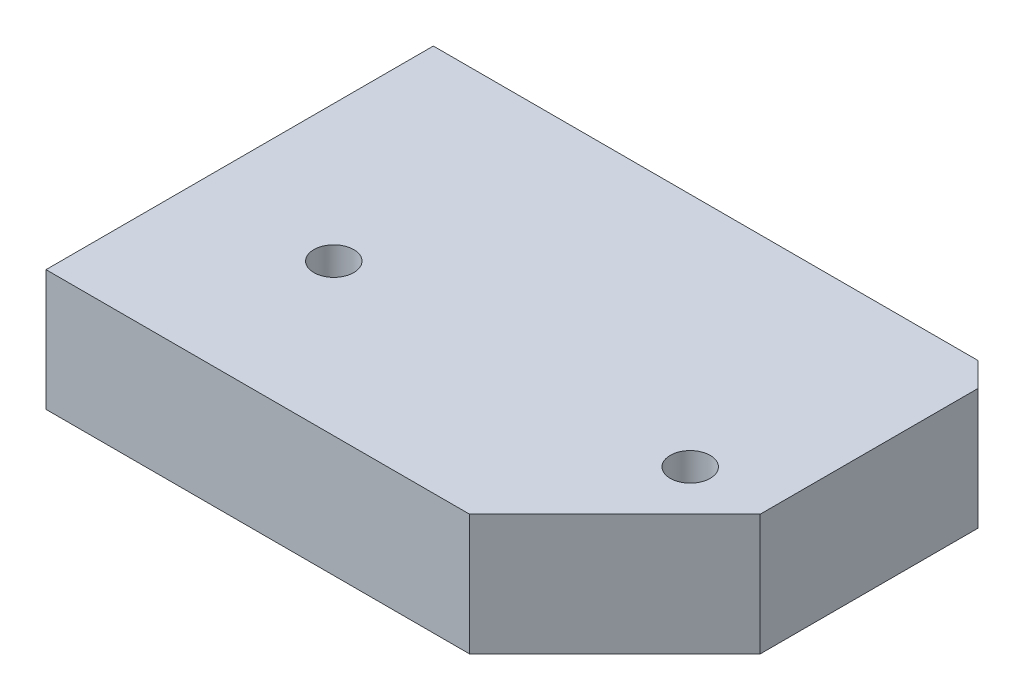
SolidWorks part; units mm, degrees
material "6061"
ref_plane "前视" through (0, 0, 0) normal (0, 0, 1) x (1, 0, 0)
ref_plane "上视" through (0, 0, 0) normal (0, 1, 0) x (1, 0, 0)
ref_plane "右视" through (0, 0, 0) normal (1, 0, 0) x (0, 0, -1)
sketch "草图1" plane through (0, 0, 0) normal (1, 0, 0) x (0, 0, -1)
  line L1 (-21, -5) -> (21, -5)
  line L2 (-21, -5) -> (-21, 5)
  line L3 (-21, 5) -> (21, 5)
  line L4 (21, -5) -> (21, 5)
  line L5 (-21, -5) -> (21, 5) construction
  line L6 (-21, 5) -> (21, -5) construction
  point P0 (0, 0)
  dimension "D1" = 42
  dimension "D2" = 10
extrude "凸台-拉伸1" add sketch "草图1" along normal mid plane 47
sketch "草图2" plane through (23.5, 0, 0) normal (1, 0, 0) x (0, 0, -1)
  line L0 (21, -5) -> (11, 5)
  line L1 (21, 5) -> (-21, 5) construction
  line L2 (11, 5) -> (21, 5)
  line L3 (21, 5) -> (21, -5)
extrude "切除-拉伸1" cut sketch "草图2" against normal through all
hole_wizard "M4 螺纹孔2" positions "草图5" profile "草图4" tap size "M4" standard "Gb"
sketch "草图5" plane through (-23.5, -27.8631, 2.4586) normal (1, 0, 0) x (0, -1, 0)
  line L0 (-32.8631, 0.4586) -> (-27.8631, 0.4586) construction
  line L1 (-32.8631, 13.4586) -> (-32.8631, -18.5414) construction
  line L2 (-27.8631, 0.4586) -> (-27.8631, -18.5414) construction
  line L6 (-32.8631, -18.5414) -> (-22.8631, -18.5414) construction
  point P0 (-27.8631, -5.5414)
  point P15 (-27.8631, 6.4586)
  dimension "D1" = 12
  dimension "D2" = 23
sketch "草图4" plane through (-23.5, 0, 8) normal (0, 1, 0) x (0, 0, 1)
  line L0 (0, 0) -> (0, 11.0914)
  line L1 (0, 11.0914) -> (1.65, 10.1)
  line L2 (1.65, 10.1) -> (1.65, 0)
  line L5 (1.65, 0) -> (0, 0)
  line L10 (0, 11.0914) -> (-1.65, 10.1) construction
  line L11 (0, -6.35) -> (0, 107.95) construction
  dimension "螺纹孔钻头直径" = 3.3
  dimension "螺纹孔钻头深度" = 10.1
  dimension "导头角度" = 118
cosmetic thread "孔螺蚊线6" parameters "D1"=8, "D2"=4
cosmetic thread "孔螺蚊线7" parameters "D1"=8, "D2"=4
hole_wizard "M4 螺纹孔1" positions "草图7" profile "草图6" tap size "M4" standard "Gb" end condition through all
sketch "草图7" plane through (0, -5, 0) normal (0, -1, 0) x (-1, 0, 0)
  line L1 (-23.5, -21) -> (23.5, -21) construction
  line L2 (-2.5, 0) -> (-17.2224, -8.5) construction
  line L3 (-2.5, 0) -> (-2.5, -15.3388) construction
  line L5 (-23.5, -21) -> (-23.5, 21) construction
  circle A0 centre (-2.5, 0) radius 17 construction
  point P0 (-2.5, 17)
  point P18 (-17.2224, -8.5)
  point P23 (12.2224, -8.5)
  dimension "D1" = 34
  dimension "D2" = 21
  dimension "D3" = 21
  dimension "D4" = 60
sketch "草图6" plane through (2.5, -5, -17) normal (1, 0, 0) x (0, 0, -1)
  line L0 (0, 0) -> (0, 10)
  line L1 (0, 10) -> (1.65, 10)
  line L2 (1.65, 10) -> (1.65, 0)
  line L5 (1.65, 0) -> (0, 0)
  line L11 (0, -6.35) -> (0, 107.95) construction
  dimension "通孔螺纹孔钻头直径" = 3.3
  dimension "通孔螺纹孔钻头深度" = 10
cosmetic thread "孔螺蚊线2" parameters "D2"=4
cosmetic thread "孔螺蚊线4" parameters "D2"=4
cosmetic thread "孔螺蚊线5" parameters "D2"=4
chamfer "倒角4" distance 12 angle 45 1 edges at (23.5, 0, 21)
sketch "草图8" plane through (0, -5, 0) normal (0, -1, 0) x (1, 0, 0)
  line L0 (23.5, -9) -> (11.5, -21)
  line L1 (23.5, 9) -> (23.5, -21) construction
  line L2 (23.5, -21) -> (-23.5, -21) construction
  line L3 (11.5, -21) -> (23.5, -21)
  line L4 (23.5, -21) -> (23.5, -9)
  dimension "D1" = 12
extrude "切除-拉伸3" cut sketch "草图8" against normal through all
